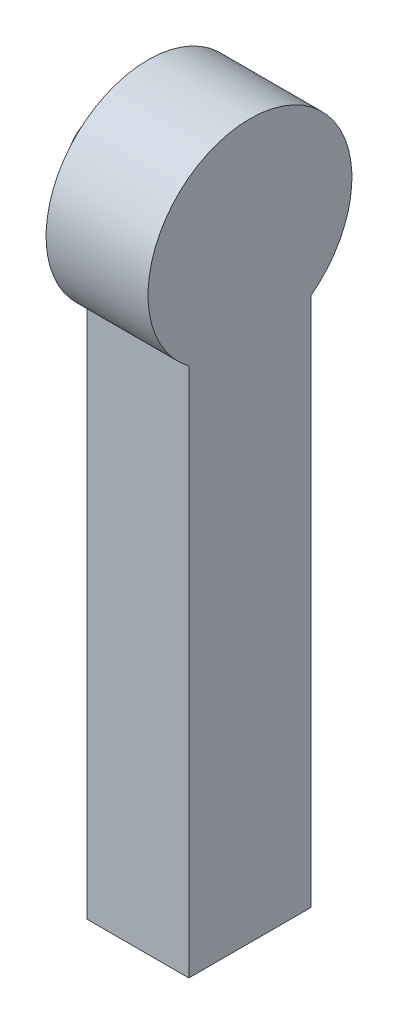
SolidWorks part; units mm, degrees
ref_plane "前视基准面" through (0, 0, 0) normal (0, 0, 1) x (1, 0, 0)
ref_plane "上视基准面" through (0, 0, 0) normal (0, 1, 0) x (1, 0, 0)
ref_plane "右视基准面" through (0, 0, 0) normal (1, 0, 0) x (0, 0, -1)
sketch "草图1" plane through (0, 0, 0) normal (1, 0, 0) x (0, 0, -1)
  circle A0 centre (0, 0) radius 1.5
  point P3 (0, 0)
extrude "凸台-拉伸1" add sketch "草图1" along normal blind 2.5
sketch "草图2" plane through (2.5, 0, 0) normal (1, 0, 0) x (0, 0, -1)
  circle A0 centre (0, 0) radius 5
extrude "凸台-拉伸2" add sketch "草图2" along normal blind 5
sketch "草图3" plane through (0, 0, 0) normal (0, 1, 0) x (1, 0, 0)
  line L0 (2.5, 5) -> (2.5, -5) construction
  line L1 (2.5, 3) -> (7.5, 3)
  line L2 (2.5, 3) -> (2.5, -3)
  line L3 (2.5, -3) -> (7.5, -3)
  line L4 (7.5, 3) -> (7.5, -3)
  line L5 (7.5, -5) -> (7.5, 5) construction
extrude "凸台-拉伸3" add sketch "草图3" against normal blind 30
